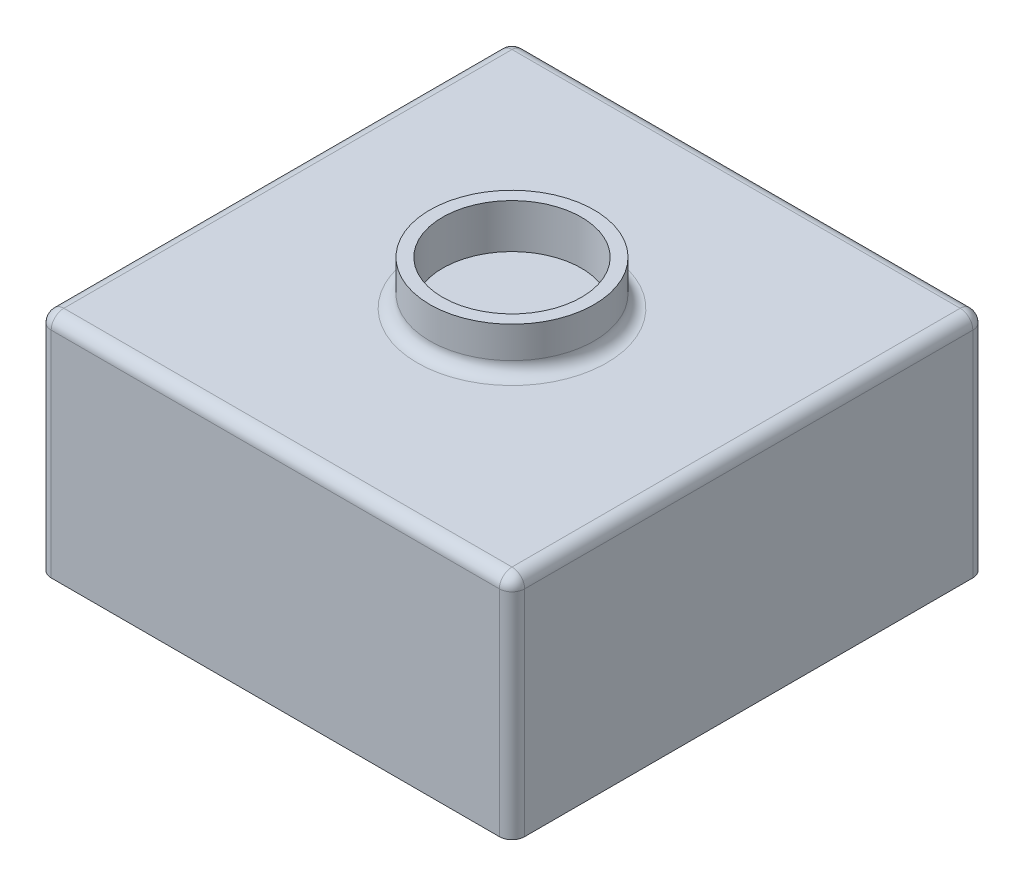
SolidWorks part; units mm, degrees
material "AISI 1020"
ref_plane "Front Plane" through (0, 0, 0) normal (0, 0, 1) x (1, 0, 0)
ref_plane "Top Plane" through (0, 0, 0) normal (0, 1, 0) x (1, 0, 0)
ref_plane "Right Plane" through (0, 0, 0) normal (1, 0, 0) x (0, 0, -1)
sketch "Sketch1" plane through (0, 0, 0) normal (0, 1, 0) x (1, 0, 0)
  line L1 (187.5, -187.5) -> (-187.5, -187.5)
  line L2 (187.5, -187.5) -> (187.5, 187.5)
  line L3 (187.5, 187.5) -> (-187.5, 187.5)
  line L4 (-187.5, -187.5) -> (-187.5, 187.5)
  line L5 (187.5, -187.5) -> (-187.5, 187.5) construction
  line L6 (187.5, 187.5) -> (-187.5, -187.5) construction
  point P0 (0, 0)
  dimension "D1" = 375
  dimension "D2" = 375
extrude "Boss-Extrude1" add sketch "Sketch1" along normal blind 180
sketch "Sketch2" plane through (0, 180, 0) normal (0, 1, 0) x (1, 0, 0)
  circle A0 centre (0, 0) radius 65
  dimension "D1" = 130
extrude "Boss-Extrude2" add sketch "Sketch2" along normal blind 35
sketch "Sketch3" plane through (0, 215, 0) normal (0, 1, 0) x (1, 0, 0)
  circle A0 centre (0, 0) radius 55
  dimension "D1" = 110
extrude "Cut-Extrude1" cut sketch "Sketch3" against normal up to surface (35 mm away) up to face at (0, 180, 65)
fillet "Fillet1" radius 10 1 edges at (0, 180, 65)
fillet "Fillet2" radius 10 8 edges at (187.5, 90, 187.5) (187.5, 180, 0) (187.5, 90, -187.5) (0, 180, -187.5) (-187.5, 90, -187.5) (-187.5, 180, 0) (0, 180, 187.5) (-187.5, 90, 187.5)
